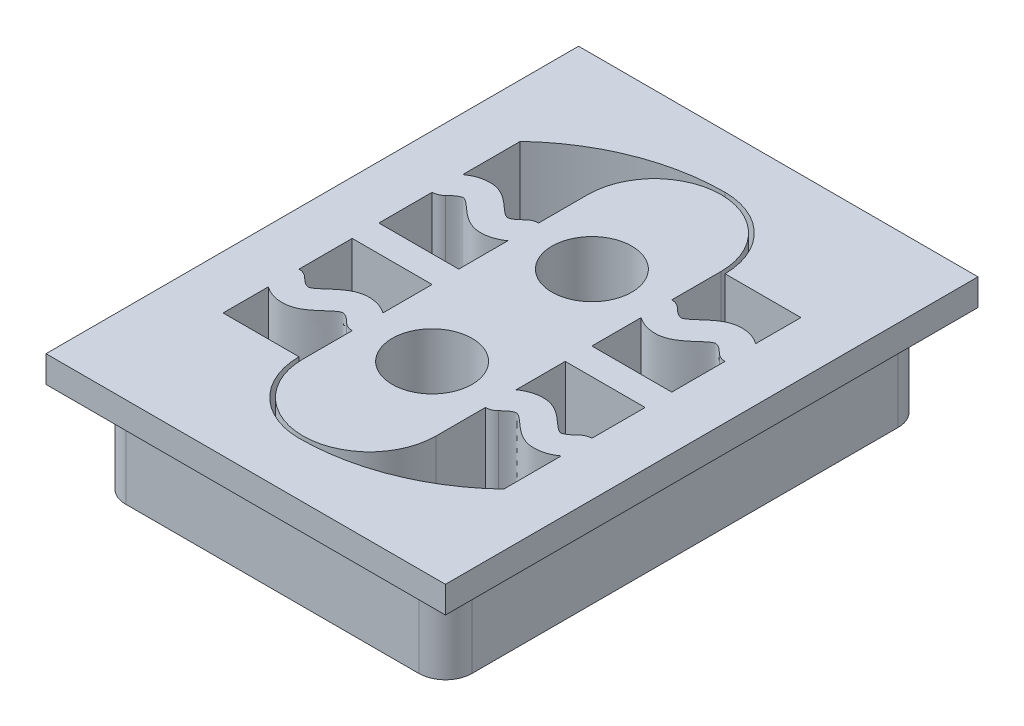
SolidWorks part; units mm, degrees
ref_plane "Front Plane" through (0, 0, 0) normal (0, 0, 1) x (1, 0, 0)
ref_plane "Top Plane" through (0, 0, 0) normal (0, 1, 0) x (1, 0, 0)
ref_plane "Right Plane" through (0, 0, 0) normal (1, 0, 0) x (0, 0, -1)
sketch "Sketch1" plane through (0, 0, 0) normal (0, 1, 0) x (1, 0, 0)
  line L1 (-6.5, -9) -> (6.5, -9)
  line L2 (-6.5, -9) -> (-6.5, 9)
  line L3 (-6.5, 9) -> (6.5, 9)
  line L4 (6.5, -9) -> (6.5, 9)
  line L5 (-6.5, -9) -> (6.5, 9) construction
  line L6 (-6.5, 9) -> (6.5, -9) construction
  point P0 (0, 0)
  dimension "D1" = 18
  dimension "D2" = 13
extrude "Boss-Extrude1" add sketch "Sketch1" along normal blind 3.4
sketch "Sketch2" plane through (0, 3.4, 0) normal (0, 1, 0) x (1, 0, 0)
  line L8 (7.5, -10) -> (7.5, 10)
  line L9 (7.5, 10) -> (-7.5, 10)
  line L10 (-7.5, 10) -> (-7.5, -10)
  line L11 (-7.5, -10) -> (7.5, -10)
  line L12 (7.5, -10) -> (7.5, 10)
  line L13 (7.5, 10) -> (-7.5, 10)
  line L14 (-7.5, 10) -> (-7.5, -10)
  line L15 (-7.5, -10) -> (7.5, -10)
  dimension "D1" = 1
extrude "Boss-Extrude2" add sketch "Sketch2" along normal blind 1
sketch "Sketch4" plane through (0, 0, 0) normal (0, -1, 0) x (1, 0, 0)
  line L4 (0, -3) -> (0, 3)
  line L5 (-2.65, 5.35) -> (-5.5, 5.35)
  line L6 (2.5, -5.35) -> (-2.5, -5.35)
  line L7 (2.5, -5.35) -> (2.5, 5.35)
  line L8 (5.5, -8) -> (5.5, 8)
  line L9 (5.5, 8) -> (-5.5, 8)
  line L10 (-5.5, 8) -> (-5.5, -8)
  line L11 (-5.5, -8) -> (5.5, -8)
  line L12 (5.5, -8) -> (5.5, 8)
  line L13 (5.5, 8) -> (-5.5, 8)
  line L14 (-5.5, 8) -> (-5.5, -8)
  line L15 (-5.5, -8) -> (5.5, -8)
  line L16 (2.5, 5.35) -> (-2.5, 5.35)
  line L17 (-2.5, -5.35) -> (-2.5, 5.35)
  line L18 (2.5, -5.35) -> (-2.5, 5.35) construction
  line L19 (2.5, 5.35) -> (-2.5, -5.35) construction
  line L20 (2.65, -5.35) -> (5.5, -5.35)
  line L21 (-4.2, 8) -> (-4.2, -8) construction
  line L22 (-3.8, -8) -> (-3.8, 8) construction
  line L23 (-5.5, 3) -> (-2.5, 3) construction
  line L24 (-4.2, 3.1728) -> (-4.2, 3) construction
  line L25 (-3.8, 2.8272) -> (-3.8, 3) construction
  line L26 (-4.2, 3.1728) -> (-4.2, 3)
  line L27 (-3.8, 3) -> (-3.8, 2.8272)
  line L28 (-2.5, 0) -> (-5.5, 0)
  line L29 (2.5, 0) -> (5.5, 0)
  line L30 (-2.5, 0.5) -> (-5.5, 0.5)
  line L31 (2.5, -0.5) -> (5.5, -0.5)
  line L32 (-2.5, -0.5) -> (-5.5, -0.5)
  line L33 (2.5, 0.5) -> (5.5, 0.5)
  circle A0 centre (0, 3) radius 1.5
  circle A1 centre (0, -3) radius 1.5
  arc A2 (-2.5, 5.35) -> (2.5, 5.35) centre (0, 5.35) cw
  arc A3 (-2.5, -5.35) -> (2.5, -5.35) centre (0, -5.35) ccw
  arc A4 (0, 8) -> (-2.65, 5.35) centre (0, 5.35) ccw
  arc A5 (0, 8) -> (5.5, 5.8095) centre (0, 0) cw
  arc A6 (0, -8) -> (2.65, -5.35) centre (0, -5.35) ccw
  arc A7 (0, -8) -> (-5.5, -5.8095) centre (0, 0) cw
  arc A8 (-5.1475, 2.6454) -> (-5.8525, 3.3546) centre (-5.5, 3) cw
  arc A9 (-2.1475, 2.6454) -> (-2.8525, 3.3546) centre (-2.5, 3) ccw
  arc A10 (5.8525, 3.3546) -> (5.1475, 2.6454) centre (5.5, 3) cw
  arc A11 (2.8525, 3.3546) -> (2.1475, 2.6454) centre (2.5, 3) ccw
  arc A12 (5.1475, -2.6454) -> (5.8525, -3.3546) centre (5.5, -3) cw
  arc A13 (2.1475, -2.6454) -> (2.8525, -3.3546) centre (2.5, -3) ccw
  arc A14 (-5.8525, -3.3546) -> (-5.1475, -2.6454) centre (-5.5, -3) cw
  arc A15 (-2.8525, -3.3546) -> (-2.1475, -2.6454) centre (-2.5, -3) ccw
  arc A16 (-2.5, 0.5) -> (-2.5, -0.5) centre (-2.5, 0) cw
  arc A17 (-5.5, 0.5) -> (-5.5, -0.5) centre (-5.5, 0) ccw
  arc A18 (2.5, -0.5) -> (2.5, 0.5) centre (2.5, 0) cw
  arc A19 (5.5, -0.5) -> (5.5, 0.5) centre (5.5, 0) ccw
  spline S0 degree 3 poles (-5.5, 3) (-4.0778, 4.4136) (-3.9222, 1.5864) (-2.5, 3) knots 0 0 0 0 1 1 1 1
  spline S1 degree 3 poles (5.5, 3) (4.0778, 4.4136) (3.9222, 1.5864) (2.5, 3) knots 0 0 0 0 1 1 1 1
  spline S2 degree 3 poles (5.5, -3) (4.0778, -4.4136) (3.9222, -1.5864) (2.5, -3) knots 0 0 0 0 1 1 1 1
  spline S3 degree 3 poles (-5.5, -3) (-4.0778, -4.4136) (-3.9222, -1.5864) (-2.5, -3) knots 0 0 0 0 1 1 1 1
  spline S4 degree 1 poles (-5.1475, 2.6454) (-2.1475, 2.6454) knots 0 0 1 1 construction
  spline S5 degree 3 poles (-5.1475, 2.6454) (-5.0875, 2.7051) (-4.9388, 2.8332) (-4.8159, 2.8957) (-4.7521, 2.9097) (-4.7197, 2.9084) (-4.6067, 2.8672) (-4.3449, 2.64) (-4.0157, 2.3383) (-3.4967, 2.0501) (-2.883, 2.1138) (-2.462, 2.3606) (-2.245, 2.5485) (-2.1475, 2.6454) knots 0 0 0 0 0.0625 0.125 0.1875 0.25 0.375 0.5 0.625 0.75 0.875 0.9375 1 1 1 1
  spline S6 degree 1 poles (-5.8525, 3.3546) (-2.8525, 3.3546) knots 0 0 1 1 construction
  spline S7 degree 3 poles (-5.8525, 3.3546) (-5.755, 3.4515) (-5.538, 3.6394) (-5.117, 3.8862) (-4.5033, 3.9499) (-3.9843, 3.6617) (-3.6551, 3.36) (-3.3933, 3.1328) (-3.2803, 3.0916) (-3.2479, 3.0903) (-3.1841, 3.1043) (-3.0612, 3.1668) (-2.9125, 3.2949) (-2.8525, 3.3546) knots 0 0 0 0 0.0625 0.125 0.25 0.375 0.5 0.625 0.75 0.8125 0.875 0.9375 1 1 1 1
  spline S8 degree 1 poles (5.8525, 3.3546) (2.8525, 3.3546) knots 0 0 1 1 construction
  spline S9 degree 3 poles (5.8525, 3.3546) (5.755, 3.4515) (5.538, 3.6394) (5.117, 3.8862) (4.5033, 3.9499) (3.9843, 3.6617) (3.6551, 3.36) (3.3933, 3.1328) (3.2803, 3.0916) (3.2479, 3.0903) (3.1841, 3.1043) (3.0612, 3.1668) (2.9125, 3.2949) (2.8525, 3.3546) knots 0 0 0 0 0.0625 0.125 0.25 0.375 0.5 0.625 0.75 0.8125 0.875 0.9375 1 1 1 1
  spline S10 degree 1 poles (5.1475, -2.6454) (2.1475, -2.6454) knots 0 0 1 1 construction
  spline S11 degree 3 poles (5.1475, -2.6454) (5.0875, -2.7051) (4.9388, -2.8332) (4.8159, -2.8957) (4.7521, -2.9097) (4.7197, -2.9084) (4.6067, -2.8672) (4.3449, -2.64) (4.0157, -2.3383) (3.4967, -2.0501) (2.883, -2.1138) (2.462, -2.3606) (2.245, -2.5485) (2.1475, -2.6454) knots 0 0 0 0 0.0625 0.125 0.1875 0.25 0.375 0.5 0.625 0.75 0.875 0.9375 1 1 1 1
  spline S12 degree 1 poles (-5.8525, -3.3546) (-2.8525, -3.3546) knots 0 0 1 1 construction
  spline S13 degree 3 poles (-5.8525, -3.3546) (-5.755, -3.4515) (-5.538, -3.6394) (-5.117, -3.8862) (-4.5033, -3.9499) (-3.9843, -3.6617) (-3.6551, -3.36) (-3.3933, -3.1328) (-3.2803, -3.0916) (-3.2479, -3.0903) (-3.1841, -3.1043) (-3.0612, -3.1668) (-2.9125, -3.2949) (-2.8525, -3.3546) knots 0 0 0 0 0.0625 0.125 0.25 0.375 0.5 0.625 0.75 0.8125 0.875 0.9375 1 1 1 1
  spline S14 degree 1 poles (5.1475, 2.6454) (2.1475, 2.6454) knots 0 0 1 1 construction
  spline S15 degree 3 poles (5.1475, 2.6454) (5.0875, 2.7051) (4.9388, 2.8332) (4.8159, 2.8957) (4.7521, 2.9097) (4.7197, 2.9084) (4.6067, 2.8672) (4.3449, 2.64) (4.0157, 2.3383) (3.4967, 2.0501) (2.883, 2.1138) (2.462, 2.3606) (2.245, 2.5485) (2.1475, 2.6454) knots 0 0 0 0 0.0625 0.125 0.1875 0.25 0.375 0.5 0.625 0.75 0.875 0.9375 1 1 1 1
  spline S16 degree 1 poles (5.8525, -3.3546) (2.8525, -3.3546) knots 0 0 1 1 construction
  spline S17 degree 3 poles (5.8525, -3.3546) (5.755, -3.4515) (5.538, -3.6394) (5.117, -3.8862) (4.5033, -3.9499) (3.9843, -3.6617) (3.6551, -3.36) (3.3933, -3.1328) (3.2803, -3.0916) (3.2479, -3.0903) (3.1841, -3.1043) (3.0612, -3.1668) (2.9125, -3.2949) (2.8525, -3.3546) knots 0 0 0 0 0.0625 0.125 0.25 0.375 0.5 0.625 0.75 0.8125 0.875 0.9375 1 1 1 1
  spline S18 degree 1 poles (-5.1475, -2.6454) (-2.1475, -2.6454) knots 0 0 1 1 construction
  spline S19 degree 3 poles (-5.1475, -2.6454) (-5.0875, -2.7051) (-4.9388, -2.8332) (-4.8159, -2.8957) (-4.7521, -2.9097) (-4.7197, -2.9084) (-4.6067, -2.8672) (-4.3449, -2.64) (-4.0157, -2.3383) (-3.4967, -2.0501) (-2.883, -2.1138) (-2.462, -2.3606) (-2.245, -2.5485) (-2.1475, -2.6454) knots 0 0 0 0 0.0625 0.125 0.1875 0.25 0.375 0.5 0.625 0.75 0.875 0.9375 1 1 1 1
  point P3 (0, 0)
  point P5 (0, 0)
  dimension "D3" = 3
  dimension "D6" = 1.3
  dimension "D8" = 3.5
  dimension "D2" = 6
  dimension "D4" = 10.7
  dimension "D5" = 5
  dimension "D7" = 1.3
  dimension "D9" = 0.5
  dimension "D1" = 1
  dimension "D10" = 0.5
  dimension "D11" = 0.5
  dimension "D12" = 0.5
extrude "Cut-Extrude2" cut sketch "Sketch4" against normal blind 10
fillet "Fillet1" radius 1 4 edges at (6.5, 1.7, 9) (6.5, 1.7, -9) (-6.5, 1.7, -9) (-6.5, 1.7, 9)
mirror "Mirror2" [suppressed]
delete or keep bodies "Body-Delete/Keep 2" [suppressed] type keep bodies bodies 107
mirror "Mirror1" [suppressed]
delete or keep bodies "Body-Delete/Keep 1" [suppressed] type keep bodies bodies 104
